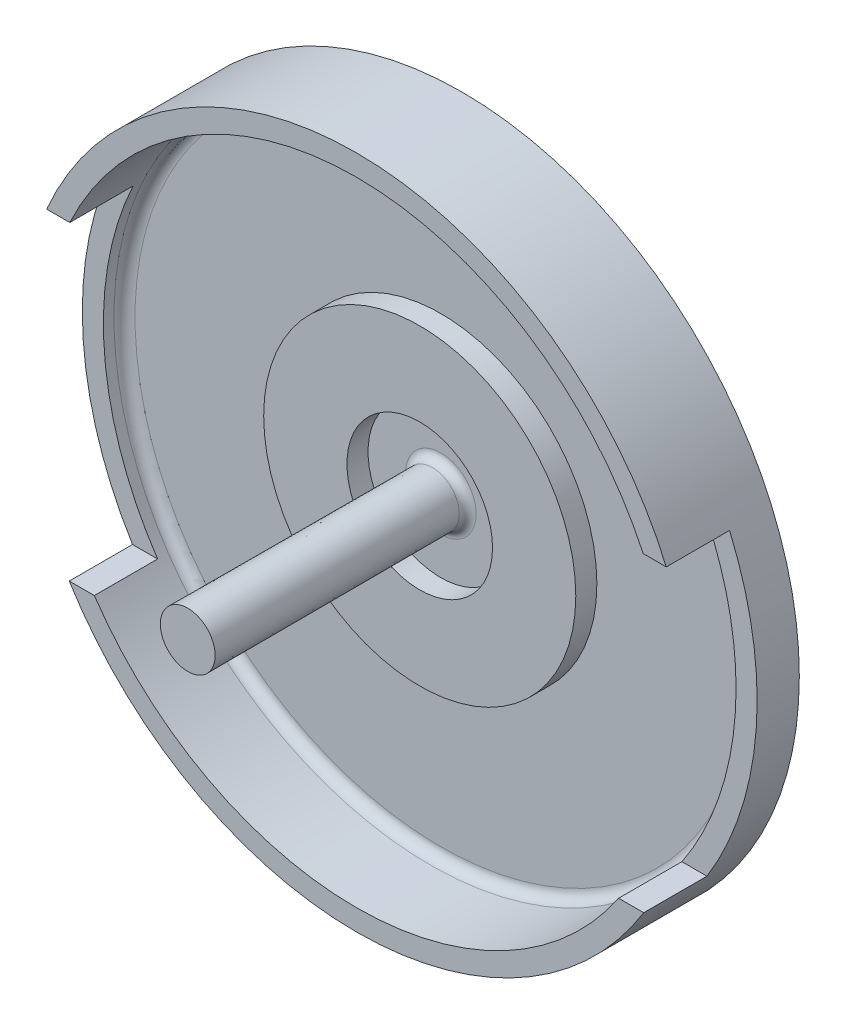
SolidWorks part; units mm, degrees
ref_plane "Front Plane" through (0, 0, 0) normal (0, 0, 1) x (1, 0, 0)
ref_plane "Top Plane" through (0, 0, 0) normal (0, 1, 0) x (1, 0, 0)
ref_plane "Right Plane" through (0, 0, 0) normal (1, 0, 0) x (0, 0, -1)
sketch "Sketch1" plane through (0, 0, 0) normal (0, 0, 1) x (1, 0, 0)
  circle A0 centre (0, 0) radius 16
extrude "Boss-Extrude1" add sketch "Sketch1" along normal blind 5
sketch "Sketch3" plane through (0, 0, 5) normal (0, 0, 1) x (1, 0, 0)
  circle A0 centre (0, 0) radius 15
extrude "Cut-Extrude1" cut sketch "Sketch3" against normal blind 4 contours A0
fillet "Fillet1" radius 0.5 1 edges at (15, 0, 1)
ref_plane "Plane4" through (0, 0, 13) normal (0, 0, 1) x (1, 0, 0)
sketch "Sketch7" plane through (0, 0, 13) normal (0, 0, 1) x (1, 0, 0)
  line L1 (-17.0905, 6.3393) -> (-11.822, 6.3393)
  line L2 (-17.0905, 6.3393) -> (-17.0905, -8.3958)
  line L3 (-17.0905, -8.3958) -> (-11.822, -8.3958)
  line L4 (-11.822, 6.3393) -> (-11.822, -8.3958)
  circle A0 centre (0, 0) radius 14.5 construction
extrude "Cut-Extrude2" cut sketch "Sketch7" against normal blind 11 contours L4 L3 L2 L1
mirror "Mirror1" about plane through (0, 0, 0) normal (1, 0, 0) of "Cut-Extrude2"
sketch "Sketch8" plane through (0, 0, 1) normal (0, 0, 1) x (1, 0, 0)
  circle A0 centre (0, 0) radius 7.4
extrude "Boss-Extrude2" add sketch "Sketch8" along normal blind 1 contours A0
sketch "Sketch9" plane through (0, 0, 2) normal (0, 0, 1) x (1, 0, 0)
  circle A0 centre (0, 0) radius 3.45
extrude "Cut-Extrude3" cut sketch "Sketch9" against normal blind 1
sketch "Sketch5" plane through (0, 0, 1) normal (0, 0, 1) x (1, 0, 0)
  circle A0 centre (0, 0) radius 1.275
  dimension "D1" = 2.55
sketch "Sketch6" plane through (0, 0, 13) normal (0, 0, 1) x (1, 0, 0)
  circle A0 centre (0, 0) radius 1.3
loft "Loft1" add profiles "Sketch5", "Sketch6"
fillet "Fillet3" radius 0.4 1 edges at (1.275, 0, 1)
